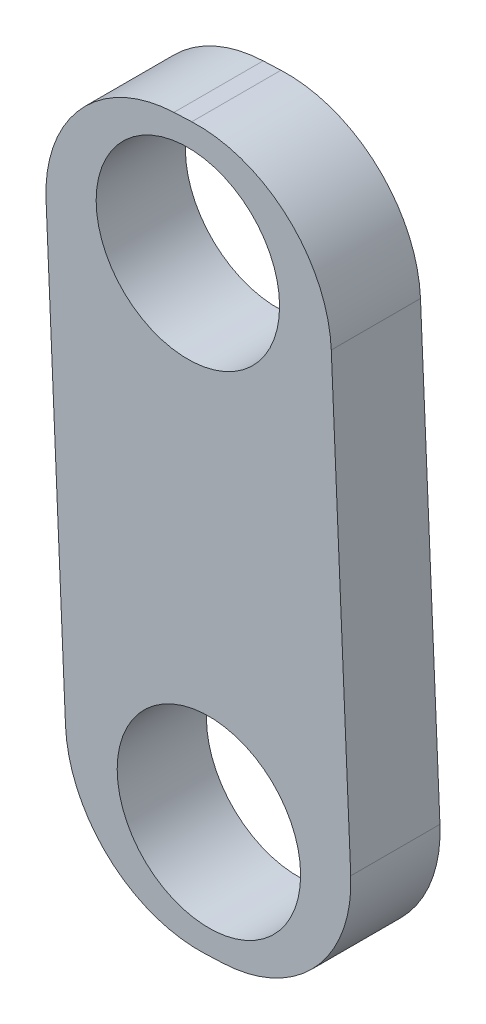
SolidWorks part; units mm, degrees
material "ABS"
ref_plane "Front Plane" through (0, 0, 0) normal (0, 0, 1) x (1, 0, 0)
ref_plane "Top Plane" through (0, 0, 0) normal (0, 1, 0) x (1, 0, 0)
ref_plane "Right Plane" through (0, 0, 0) normal (1, 0, 0) x (0, 0, -1)
sketch "Sketch1" plane through (0, 0, 0) normal (0, 0, 1) x (1, 0, 0)
  line L0 (0, 0) -> (196.85, 0) construction
  line L1 (0, 0) -> (196.1009, 17.1566) construction
  line L2 (196.1009, 17.1566) -> (196.85, 0) construction
  line L3 (196.4755, 8.5783) -> (200.9967, 21.4878) construction
  line L4 (200.9967, 21.4878) -> (196.4755, 8.5783) construction
  line L5 (196.4755, 8.5783) -> (191.9543, -4.3312) construction
  line L6 (200.9967, 21.4878) -> (190.8463, 21.0446)
  line L7 (190.8463, 21.0446) -> (196.4755, 8.5783) construction
  line L8 (196.4755, 8.5783) -> (202.1046, -3.888) construction
  line L9 (191.9543, -4.3312) -> (202.1046, -3.888)
  line L10 (191.9543, -4.3312) -> (190.8463, 21.0446)
  line L11 (200.9967, 21.4878) -> (202.1046, -3.888)
  circle A0 centre (196.85, 0) radius 3.2639
  circle A1 centre (196.1009, 17.1566) radius 3.2639
  dimension "D2" = 6.5278
  dimension "D5" = 6.5278
  dimension "D1" = 196.85
  dimension "D3" = 5
  dimension "D4" = 196.85
  dimension "D6" = 10.16
  dimension "D7" = 25.4
extrude "Boss-Extrude1" add sketch "Sketch1" along normal blind 3.175
fillet "Fillet1" radius 4.7625 4 edges at (202.1046, -3.888, 1.5875) (191.9543, -4.3312, 1.5875) (200.9967, 21.4878, 1.5875) (190.8463, 21.0446, 1.5875)
sketch "Sketch2" plane through (191.4003, 8.3567, 0) normal (-0.999, -0.0436, 0) x (0, 0, 1)
  line L0 (0, 0) -> (-0.7937, 0) construction
  line L1 (0, 7.9375) -> (0, -7.9375) construction
  circle A0 centre (-0.7937, 0) radius 3.2639
  dimension "D2" = 6.5278
  dimension "D1" = 0.7937
extrude "Cut-Extrude1" cut sketch "Sketch2" against normal blind 3.175
